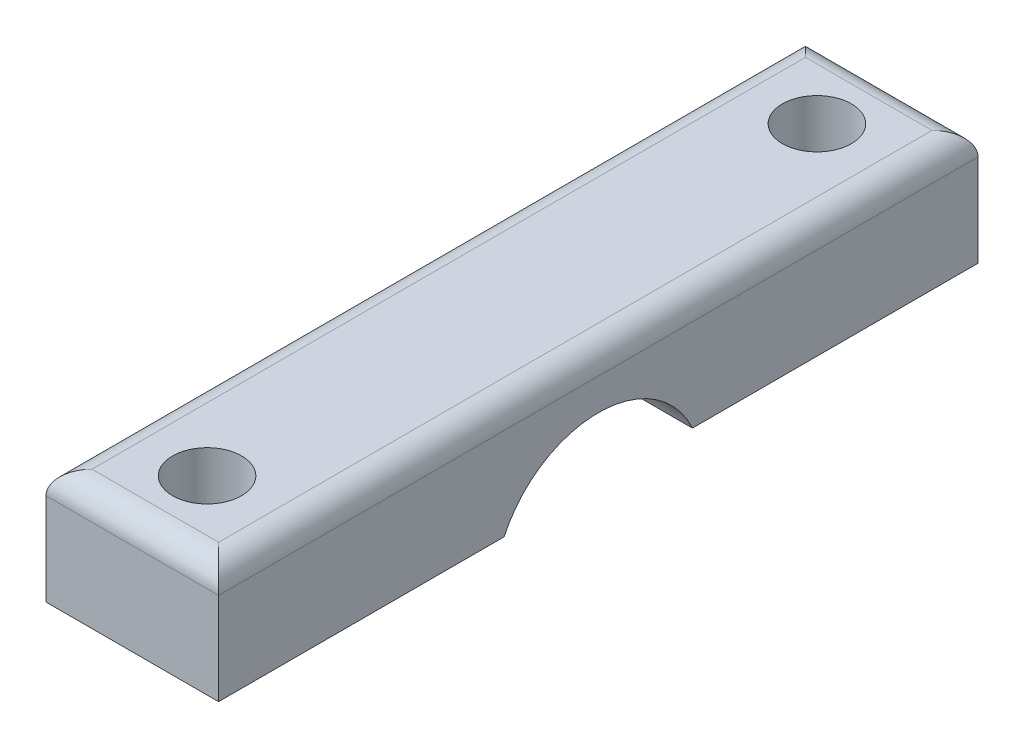
SolidWorks part; units mm, degrees
ref_plane "Front Plane" through (0, 0, 0) normal (0, 0, 1) x (1, 0, 0)
ref_plane "Top Plane" through (0, 0, 0) normal (0, 1, 0) x (1, 0, 0)
ref_plane "Right Plane" through (0, 0, 0) normal (1, 0, 0) x (0, 0, -1)
sketch "Sketch1" plane through (0, 0, 0) normal (0, 1, 0) x (1, 0, 0)
  line L0 (7.5, 66) -> (7.5, 0) construction
  line L1 (0, 0) -> (15, 0)
  line L2 (0, 0) -> (0, 66)
  line L3 (0, 66) -> (15, 66)
  line L4 (15, 0) -> (15, 66)
  line L5 (0, 33) -> (15, 33) construction
  circle A0 centre (7.5, 59.5) radius 1.75
  circle A1 centre (7.5, 6.5) radius 1.75
  dimension "D5" = 3.5
  dimension "D1" = 66
  dimension "D2" = 15
  dimension "D3" = 53
  dimension "D4" = 26.5
extrude "Boss-Extrude1" add sketch "Sketch1" along normal blind 10
sketch "Sketch2" plane through (0, 10, 0) normal (0, 1, 0) x (1, 0, 0)
  circle A0 centre (7.5, 59.5) radius 3
  circle A1 centre (7.5, 6.5) radius 3
  dimension "D1" = 6
  dimension "D2" = 6
extrude "Cut-Extrude1" cut sketch "Sketch2" against normal blind 6
fillet "Fillet1" radius 2 4 edges at (7.5, 10, -66) (0, 10, -33) (7.5, 10, 0) (15, 10, -33)
sketch "Sketch3" plane through (15, 0, 0) normal (1, 0, 0) x (0, 0, -1)
  line L0 (33, 0) -> (33, 10) construction
  line L1 (0, 0) -> (66, 0) construction
  line L2 (2, 10) -> (64, 10) construction
  circle A0 centre (33, -3.75) radius 9
  dimension "D2" = 18
  dimension "D1" = 3.75
extrude "Cut-Extrude2" cut sketch "Sketch3" against normal blind 15
